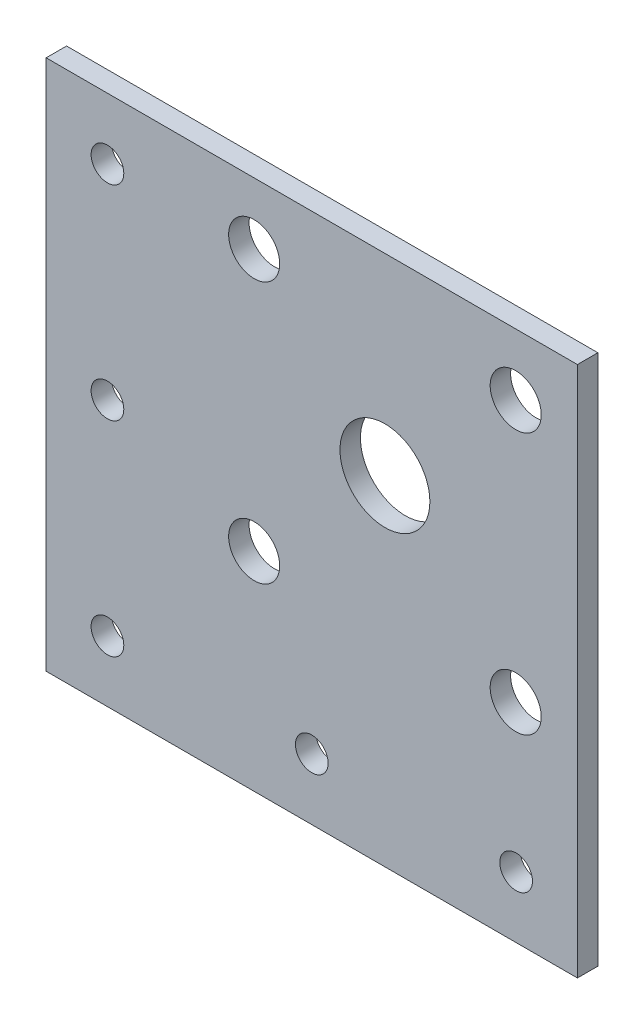
SolidWorks part; units mm, degrees
ref_plane "前视基准面" through (0, 0, 0) normal (0, 0, 1) x (1, 0, 0)
ref_plane "上视基准面" through (0, 0, 0) normal (0, 1, 0) x (1, 0, 0)
ref_plane "右视基准面" through (0, 0, 0) normal (1, 0, 0) x (0, 0, -1)
sketch "草图1" plane through (0, 0, 0) normal (0, 0, 1) x (1, 0, 0)
  line L0 (-82.9, -17.9) -> (-42.9, -17.9) construction
  line L3 (-42.9, -32.9) -> (-42.9, 32.9) construction
  line L4 (-82.9, 1957.1) -> (-82.9, -82.9) construction
  line L5 (-82.9, 47.1) -> (-82.9, -82.9)
  line L6 (-67.9, 47.1) -> (-67.9, -82.9) construction
  line L7 (-82.9, -82.9) -> (47.1, -82.9)
  line L8 (-82.9, -82.9) -> (-82.9, 47.1)
  line L9 (-82.9, 47.1) -> (47.1, 47.1)
  line L10 (47.1, -82.9) -> (47.1, 47.1)
  line L11 (-42.9, -67.9) -> (57.1, -67.9) construction
  line L13 (7.1, -67.9) -> (7.1, -50.9) construction
  line L14 (637.1, -50.9) -> (-42.9, -50.9) construction
  circle A0 centre (-32, -32) radius 6.25 construction
  circle A1 centre (-32, -32) radius 6.25
  circle A2 centre (-32, 32) radius 6.25 construction
  circle A3 centre (-32, 32) radius 6.25
  circle A4 centre (32, 32) radius 6.25 construction
  circle A5 centre (32, 32) radius 6.25
  circle A6 centre (32, -32) radius 6.25 construction
  circle A7 centre (32, -32) radius 6.25
  circle A8 centre (-67.9, 32.1) radius 4
  circle A9 centre (-67.9, -17.9) radius 4
  circle A10 centre (-67.9, -67.9) radius 4
  circle A11 centre (-17.9, -67.9) radius 4
  circle A12 centre (32.1, -67.9) radius 4
  circle A13 centre (0, 0) radius 11
  dimension "D5" = 8
  dimension "D6" = 8
  dimension "D7" = 15
  dimension "D9" = 22
  dimension "D1" = 130
  dimension "D2" = 130
  dimension "D3" = 15
  dimension "D4" = 50
  dimension "D8" = 50
extrude "凸台-拉伸1" add sketch "草图1" along normal blind 5 contours L7 L10 L9 L5 A12 A11 A1 A3 A5 A7 A8 A9 A10
